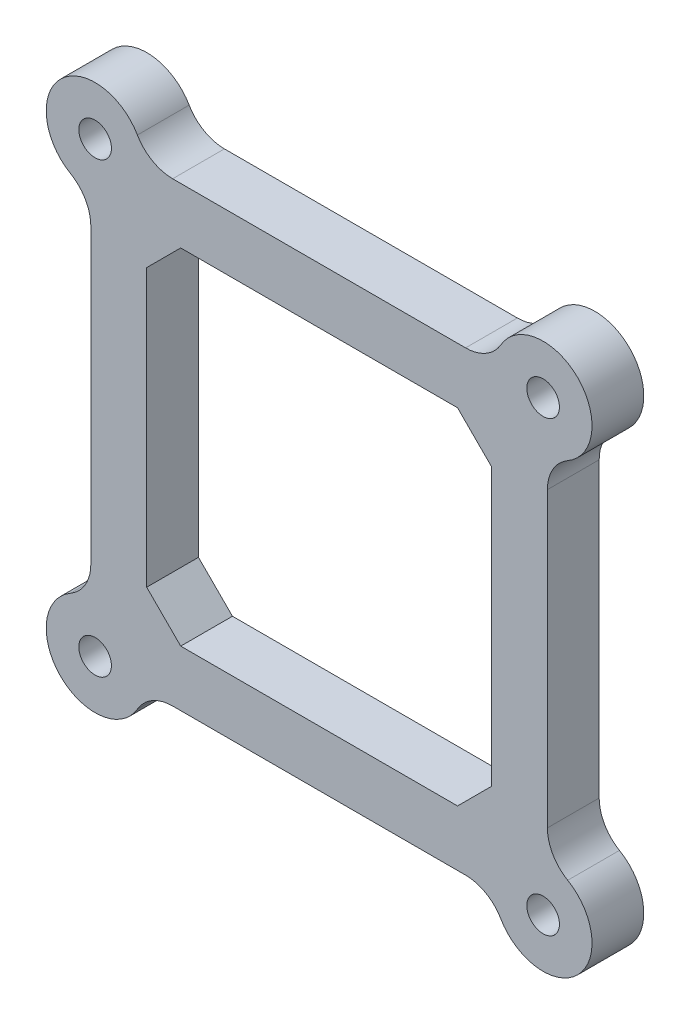
SolidWorks part; units mm, degrees
ref_plane "Plan de face" through (0, 0, 0) normal (0, 0, 1) x (1, 0, 0)
ref_plane "Plan de dessus" through (0, 0, 0) normal (0, 1, 0) x (1, 0, 0)
ref_plane "Plan de droite" through (0, 0, 0) normal (1, 0, 0) x (0, 0, -1)
sketch "Esquisse28" plane through (0, 0, 0) normal (0, 0, 1) x (1, 0, 0)
  line L0 (-21.5, -28.0054) -> (-28.0054, -21.5)
  line L1 (21.5, -28.0054) -> (-21.5, -28.0054)
  line L4 (28.0054, -21.5) -> (21.5, -28.0054)
  line L5 (28.0054, 21.5) -> (28.0054, -21.5)
  line L8 (21.5, 28.0054) -> (28.0054, 21.5)
  line L9 (-21.5, 28.0054) -> (21.5, 28.0054)
  line L10 (-28.0054, 21.5) -> (-21.5, 28.0054)
  line L11 (-28.0054, -21.5) -> (-28.0054, 21.5)
  line L16 (-16.9781, -21.15) -> (-21.15, -16.9781)
  line L17 (16.9781, -21.15) -> (-16.9781, -21.15)
  line L18 (21.15, -16.9781) -> (16.9781, -21.15)
  line L19 (21.15, 16.9781) -> (21.15, -16.9781)
  line L20 (16.9781, 21.15) -> (21.15, 16.9781)
  line L21 (-16.9781, 21.15) -> (16.9781, 21.15)
  line L22 (-21.15, 16.9781) -> (-16.9781, 21.15)
  line L23 (-21.15, -16.9781) -> (-21.15, 16.9781)
  point P1 (0, -21.15)
  point P2 (0, -28.0054)
  point P3 (28.0054, 0)
  point P24 (21.15, 0)
  dimension "D1" = 42.3
  dimension "D2" = 5.9
  dimension "D3" = 135
  dimension "D4" = 135
  dimension "D5" = 43
  dimension "D6" = 9.2
  dimension "D7" = 135
  dimension "D8" = 135
extrude "Boss.-Extru.2" add sketch "Esquisse28" along normal blind 6.35
sketch "Esquisse29" plane through (0, 0, 0) normal (0, 0, 1) x (1, 0, 0)
  line L0 (-46.0327, -46.0327) -> (46.0327, 46.0327) construction
  line L1 (-59.4617, 0) -> (59.4617, 0) construction
  circle A0 centre (27.4767, 27.4767) radius 6
  point P4 (0, 0)
  point P8 (0, 0)
  dimension "D2" = 12
  dimension "D1" = 45
extrude "Boss.-Extru.3" add sketch "Esquisse29" along normal up to surface (6.35 mm away) up to face at (0, 0, 6.35)
mirror "Symétrie1" about plane through (0, 0, 0) normal (1, 0, 0) of "Boss.-Extru.3"
mirror "Symétrie2" about plane through (0, 0, 0) normal (0, 1, 0) of "Symétrie1", "Boss.-Extru.3"
sketch "Esquisse30" plane through (0, 0, 6.35) normal (0, 0, 1) x (1, 0, 0)
  circle A0 centre (-27.4767, 27.4767) radius 2
  circle A1 centre (27.4767, 27.4767) radius 2
  circle A2 centre (27.4767, -27.4767) radius 2
  circle A3 centre (-27.4767, -27.4767) radius 2
  arc A4 (-28.0054, -21.5) -> (-21.5, -28.0054) centre (-27.4767, -27.4767) ccw construction
  arc A5 (-21.5, 28.0054) -> (-28.0054, 21.5) centre (-27.4767, 27.4767) ccw construction
  arc A6 (28.0054, 21.5) -> (21.5, 28.0054) centre (27.4767, 27.4767) ccw construction
  arc A7 (21.5, -28.0054) -> (28.0054, -21.5) centre (27.4767, -27.4767) ccw construction
  dimension "D1" = 4
extrude "Enlèv. mat.-Extru.1" cut sketch "Esquisse30" against normal through all
fillet "Congé1" radius 5 8 edges at (28.0054, 21.5, 3.175) (28.0054, -21.5, 3.175) (21.5, -28.0054, 3.175) (-21.5, -28.0054, 3.175) (-28.0054, -21.5, 3.175) (-28.0054, 21.5, 3.175) (-21.5, 28.0054, 3.175) (21.5, 28.0054, 3.175)
sketch "Esquisse31" plane through (0, 0, 6.35) normal (0, 0, 1) x (1, 0, 0)
  line L0 (-33.4767, 33.4767) -> (-33.4767, -33.4767)
  line L1 (-33.4767, -33.4767) -> (33.4767, -33.4767)
  line L2 (33.4767, -33.4767) -> (33.4767, 33.4767)
  line L3 (33.4767, 33.4767) -> (-33.4767, 33.4767)
  arc A0 (-22.2896, 30.4923) -> (-30.4923, 22.2896) centre (-27.4767, 27.4767) ccw construction
  point P4 (33.4767, 0)
  point P6 (0, -33.4767)
